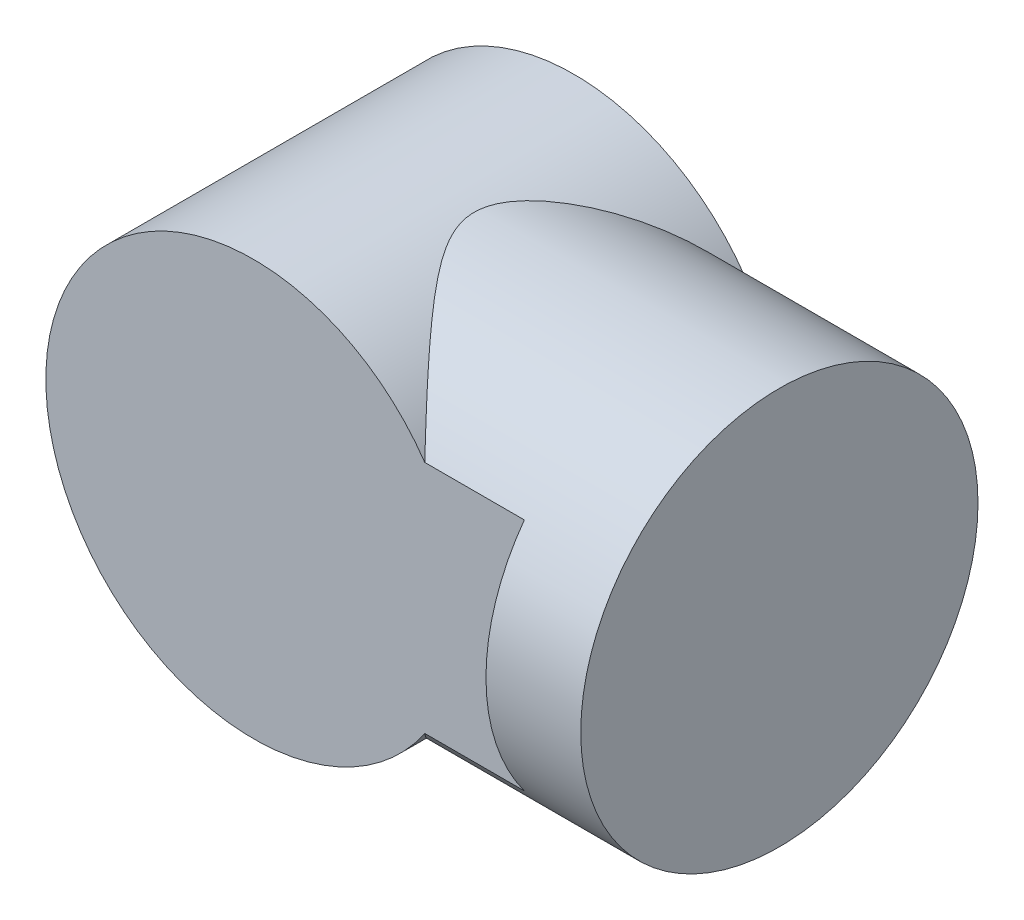
SolidWorks part; units mm, degrees
ref_plane "前视基准面" through (0, 0, 0) normal (0, 0, 1) x (1, 0, 0)
ref_plane "上视基准面" through (0, 0, 0) normal (0, 1, 0) x (1, 0, 0)
ref_plane "右视基准面" through (0, 0, 0) normal (1, 0, 0) x (0, 0, -1)
sketch "草图1" plane through (0, 0, 0) normal (0, 0, 1) x (1, 0, 0)
  circle A0 centre (0, 0) radius 46
extrude "凸台-拉伸1" add sketch "草图1" along normal mid plane 71
ref_plane "基准面1" through (81, 0, 0) normal (1, 0, 0) x (0, 0, -1)
sketch "草图2" plane through (81, 0, 0) normal (1, 0, 0) x (0, 0, -1)
  circle A0 centre (0, 0) radius 44
extrude "凸台-拉伸2" add sketch "草图2" against normal up to surface (35 mm away) up to face at (46, 0, 35.5)
sketch "草图3" plane through (0, 0, 0) normal (1, 0, 0) x (0, 0, -1)
  line L0 (-35.5, 46) -> (-35.5, -46) construction
  line L1 (-35.5, 32.4187) -> (-45.8371, 32.4187)
  line L2 (-35.5, 32.4187) -> (-35.5, -29.1983)
  line L3 (-35.5, -29.1983) -> (-45.8371, -29.1983)
  line L4 (-45.8371, 32.4187) -> (-45.8371, -29.1983)
  line L5 (35.5, -46) -> (35.5, 46) construction
  line L6 (35.5, 32.4187) -> (46.6958, 32.4187)
  line L7 (35.5, 32.4187) -> (35.5, -29.1983)
  line L8 (35.5, -29.1983) -> (46.6958, -29.1983)
  line L9 (46.6958, 32.4187) -> (46.6958, -29.1983)
extrude "切除-拉伸1" cut sketch "草图3" along normal blind 60
